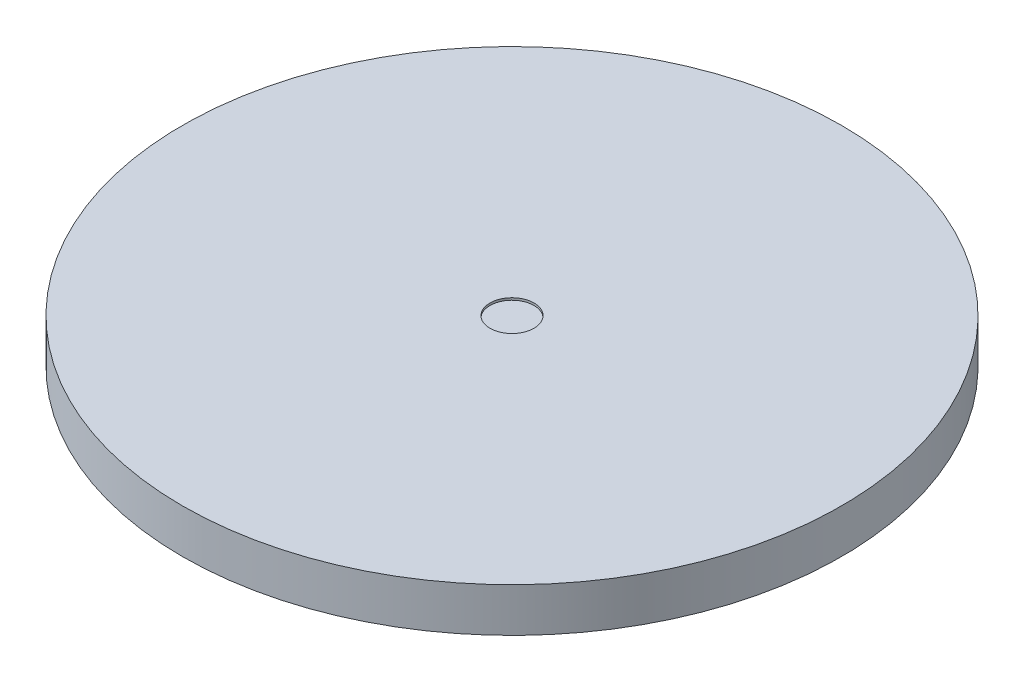
SolidWorks part; units mm, degrees
ref_plane "Front Plane" through (0, 0, 0) normal (0, 0, 1) x (1, 0, 0)
ref_plane "Top Plane" through (0, 0, 0) normal (0, 1, 0) x (1, 0, 0)
ref_plane "Right Plane" through (0, 0, 0) normal (1, 0, 0) x (0, 0, -1)
sketch "Sketch1" plane through (0, 0, 0) normal (0, 1, 0) x (1, 0, 0)
  circle A0 centre (0, 0) radius 30
extrude "Boss-Extrude1" add sketch "Sketch1" along normal blind 4
sketch "Sketch2" plane through (0, 4, 0) normal (0, 1, 0) x (1, 0, 0)
  circle A0 centre (0, 0) radius 2
extrude "Cut-Extrude1" cut sketch "Sketch2" against normal blind 0.2 contours A0
